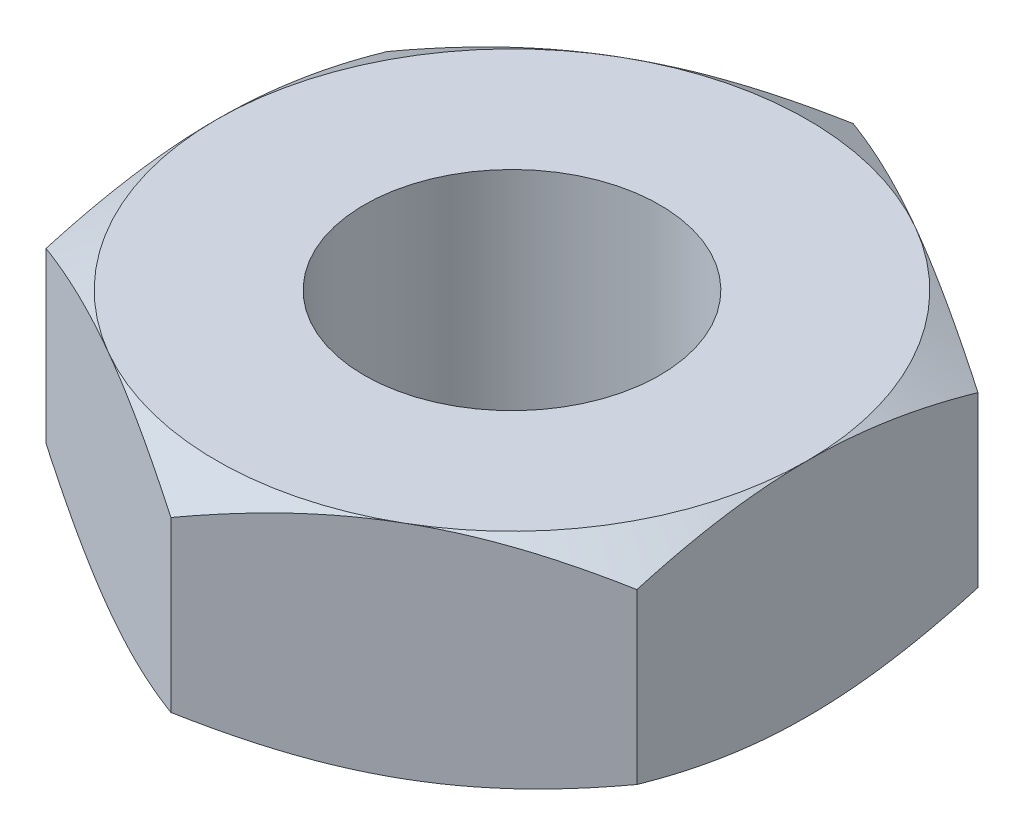
SolidWorks part; units mm, degrees
ref_plane "Front Plane" through (0, 0, 0) normal (0, 0, 1) x (1, 0, 0)
ref_plane "Top Plane" through (0, 0, 0) normal (0, 1, 0) x (1, 0, 0)
ref_plane "Right Plane" through (0, 0, 0) normal (1, 0, 0) x (0, 0, -1)
sketch "Sketch1" plane through (0, 0, 0) normal (0, 1, 0) x (1, 0, 0)
  line L1 (0, -2.3094) -> (2, -1.1547)
  line L2 (2, -1.1547) -> (2, 1.1547)
  line L3 (2, 1.1547) -> (0, 2.3094)
  line L4 (0, 2.3094) -> (-2, 1.1547)
  line L5 (-2, 1.1547) -> (-2, -1.1547)
  line L6 (-2, -1.1547) -> (0, -2.3094)
  circle A0 centre (0, 0) radius 1
  circle A1 centre (0, 0) radius 2 construction
  dimension "D1" = 2
  dimension "D2" = 4
extrude "Boss-Extrude1" add sketch "Sketch1" along normal blind 1.5
sketch "Sketch2" plane through (0, 1.5, 0) normal (0, 1, 0) x (1, 0, 0)
  circle A0 centre (0, 0) radius 2 construction
  circle A1 centre (0, 0) radius 2
extrude "Cut-Extrude1" cut sketch "Sketch2" against normal blind 2 draft 60 flip side to cut
sketch "Sketch3" plane through (0, 0, 0) normal (0, -1, 0) x (1, 0, 0)
  circle A0 centre (0, 0) radius 2 construction
  circle A1 centre (0, 0) radius 2
extrude "Cut-Extrude2" cut sketch "Sketch3" against normal blind 2 draft 60 flip side to cut
